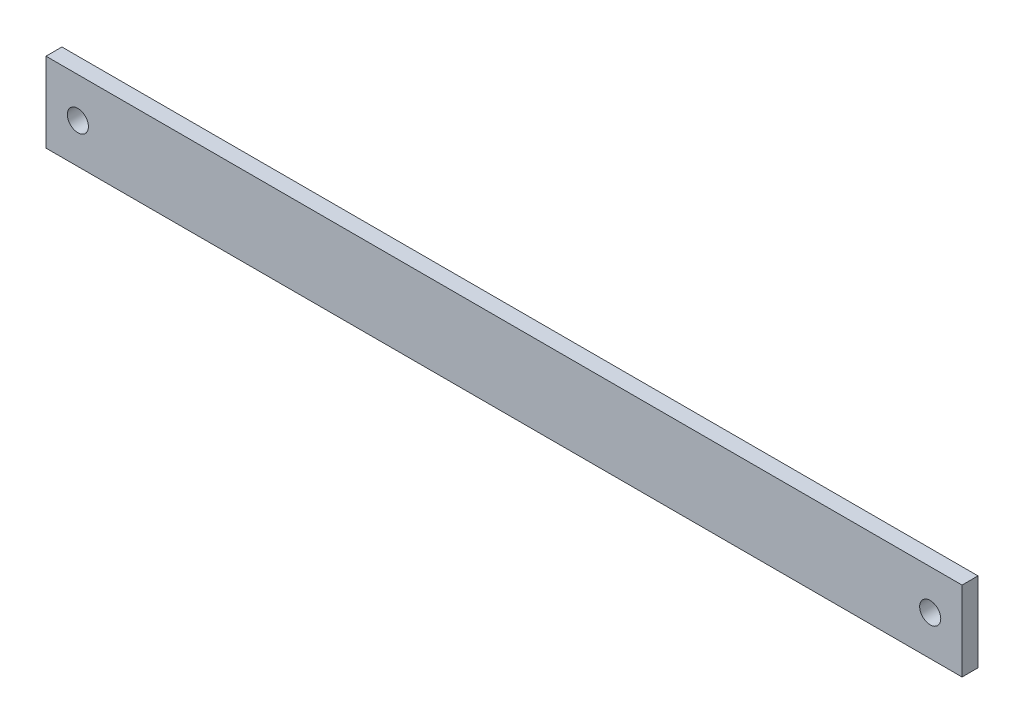
SolidWorks part; units mm, degrees
ref_plane "Front Plane" through (0, 0, 0) normal (0, 0, 1) x (1, 0, 0)
ref_plane "Top Plane" through (0, 0, 0) normal (0, 1, 0) x (1, 0, 0)
ref_plane "Right Plane" through (0, 0, 0) normal (1, 0, 0) x (0, 0, -1)
sketch "Extrusion Base Sketch" plane through (0, 0, 0) normal (0, 0, 1) x (1, 0, 0)
  line L0 (230, 20) -> (230, 0)
  line L1 (21.25, 2.5) -> (208.75, 2.5) construction
  line L2 (21.25, 2.5) -> (21.25, 17.5) construction
  line L3 (21.25, 17.5) -> (208.75, 17.5) construction
  line L4 (208.75, 2.5) -> (208.75, 17.5) construction
  line L5 (0, 20) -> (230, 20)
  line L6 (18.75, 20) -> (18.75, 0) construction
  line L7 (0, 0) -> (230, 0)
  line L8 (211.25, 20) -> (211.25, 0) construction
  line L9 (0, 20) -> (0, 0)
  line L11 (222, 10) -> (230, 10) construction
  circle A0 centre (8, 10) radius 2.65
  circle A2 centre (222, 10) radius 2.65
  point P9 (0, 0)
  point P10 (0, 0)
  point P15 (7.843, 13.9133)
  point P16 (0, 0)
  point P20 (0, 0)
  point P23 (0, 0)
  dimension "D8" = 5.3
  dimension "D1" = 15
  dimension "D2" = 187.5
  dimension "D4" = 2.5
  dimension "D5" = 2.5
  dimension "D6" = 2.5
  dimension "D3" = 20
  dimension "D7" = 21.25
extrude "Extrusion Base Extrude" add sketch "Extrusion Base Sketch" against normal blind 4
equation "\"Logo Height\"= 15mm"
equation "\"Total Height\"= 20mm"
equation "\"Border\"= ( \"Total Height\" - \"Logo Height\" ) / 2"
equation "\"Text Length\"= 187.5mm"
equation "\"D1@Extrusion Base Sketch\" = \"Logo Height\""
equation "\"D2@Extrusion Base Sketch\" = \"Text Length\""
equation "\"D4@Extrusion Base Sketch\" = \"Border\""
equation "\"D5@Extrusion Base Sketch\" = \"Border\""
equation "\"D6@Extrusion Base Sketch\" = \"Border\""
equation "\"D3@Extrusion Base Sketch\" = \"Total Height\""
